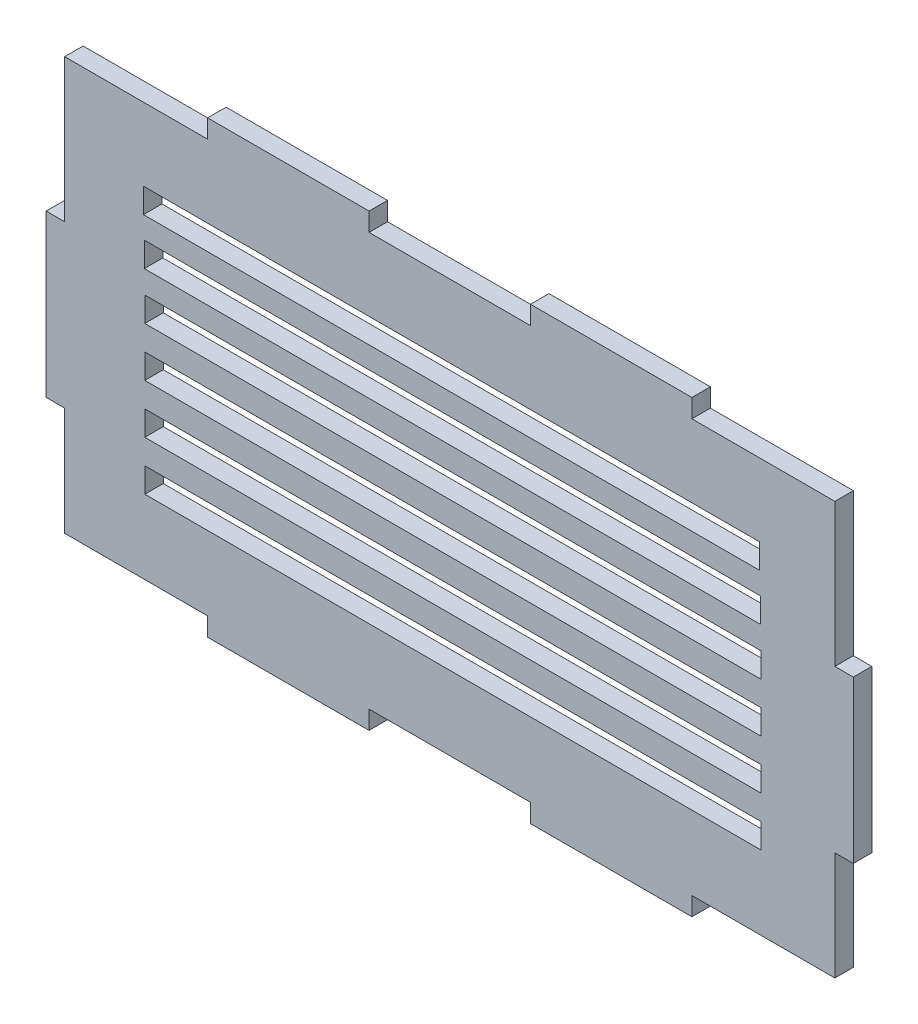
SolidWorks part; units mm, degrees
material "Acrylic (Medium-high impact)"
ref_plane "Front Plane" through (0, 0, 0) normal (0, 0, 1) x (1, 0, 0)
ref_plane "Top Plane" through (0, 0, 0) normal (0, 1, 0) x (1, 0, 0)
ref_plane "Right Plane" through (0, 0, 0) normal (1, 0, 0) x (0, 0, -1)
sketch "Sketch1" plane through (0, 0, 0) normal (0, 0, 1) x (1, 0, 0)
  line L252 (78.6, 73) -> (78.6, 70)
  line L253 (131, 73) -> (104.8, 73)
  line L255 (0, 0) -> (131, 0)
  line L256 (0, 0) -> (0, 73)
  line L257 (0, 73) -> (131, 73)
  line L258 (131, 0) -> (131, 73)
  line L290 (131, 73) -> (131, 70)
  line L291 (131, 70) -> (104.8, 70)
  line L292 (104.8, 73) -> (104.8, 70)
  line L297 (0, 73) -> (3, 73)
  line L298 (0, 73) -> (0, 46.8)
  line L299 (0, 46.8) -> (3, 46.8)
  line L300 (3, 73) -> (3, 46.8)
  line L301 (78.6, 73) -> (52.4, 73)
  line L302 (52.4, 73) -> (52.4, 70)
  line L303 (78.6, 70) -> (52.4, 70)
  line L304 (26.2, 73) -> (26.2, 70)
  line L305 (26.2, 73) -> (0, 73)
  line L306 (0, 73) -> (0, 70)
  line L307 (26.2, 70) -> (0, 70)
  line L308 (78.6, 3) -> (78.6, 0)
  line L309 (78.6, 3) -> (52.4, 3)
  line L310 (52.4, 3) -> (52.4, 0)
  line L311 (78.6, 0) -> (52.4, 0)
  line L312 (26.2, 3) -> (26.2, 0)
  line L313 (26.2, 3) -> (0, 3)
  line L314 (0, 3) -> (0, 0)
  line L315 (26.2, 0) -> (0, 0)
  line L316 (131, 3) -> (131, 0)
  line L317 (131, 3) -> (104.8, 3)
  line L318 (104.8, 3) -> (104.8, 0)
  line L319 (131, 0) -> (104.8, 0)
  line L320 (131, 73) -> (78.6, 73) construction
  line L321 (128, 73) -> (128, 46.8)
  line L322 (128, 73) -> (131, 73)
  line L323 (131, 73) -> (131, 46.8)
  line L324 (128, 46.8) -> (131, 46.8)
  line L325 (128, 20.6) -> (128, -5.6)
  line L326 (128, 20.6) -> (131, 20.6)
  line L327 (131, 20.6) -> (131, -5.6)
  line L328 (128, -5.6) -> (131, -5.6)
  line L329 (0, 20.6) -> (0, -5.6)
  line L330 (0, 20.6) -> (3, 20.6)
  line L331 (3, 20.6) -> (3, -5.6)
  line L332 (0, -5.6) -> (3, -5.6)
  line L333 (0, 73) -> (128, 73) construction
  line L334 (0, 73) -> (0, 20.6) construction
  line L335 (116, 35) -> (116, 31)
  line L336 (116, 43) -> (16, 43)
  line L337 (116, 43) -> (116, 39)
  line L338 (116, 39) -> (16, 39)
  line L339 (16, 43) -> (16, 39)
  line L340 (116, 35) -> (16, 35)
  line L341 (16, 35) -> (16, 31)
  line L342 (116, 31) -> (16, 31)
  line L343 (116, 27) -> (116, 23)
  line L344 (116, 27) -> (16, 27)
  line L345 (16, 27) -> (16, 23)
  line L346 (116, 23) -> (16, 23)
  line L347 (116, 19) -> (116, 15)
  line L348 (116, 19) -> (16, 19)
  line L349 (16, 19) -> (16, 15)
  line L350 (116, 15) -> (16, 15)
  line L351 (115.9216, 50.672) -> (15.9216, 50.672)
  line L352 (115.9216, 50.672) -> (115.9216, 46.672)
  line L353 (115.9216, 46.672) -> (15.9216, 46.672)
  line L354 (15.9216, 50.672) -> (15.9216, 46.672)
  line L355 (115.7873, 58.1915) -> (15.7873, 58.1915)
  line L356 (115.7873, 58.1915) -> (115.7873, 54.1915)
  line L357 (115.7873, 54.1915) -> (15.7873, 54.1915)
  line L358 (15.7873, 58.1915) -> (15.7873, 54.1915)
  dimension "D1" = 131
  dimension "D2" = 73
  dimension "D3" = 26.2
  dimension "D4" = 3
  dimension "D7" = 52.4
  dimension "D8" = 2
  dimension "D5" = 52.4
  dimension "D6" = 128
  dimension "D12" = 26.2
  dimension "D13" = 3
  dimension "D10" = 4
  dimension "D11" = 100
  dimension "D14" = 15
  dimension "D15" = 30
  dimension "D9" = 2
  dimension "D16" = 4
extrude "Boss-Extrude1" add sketch "Sketch1" along normal blind 3
